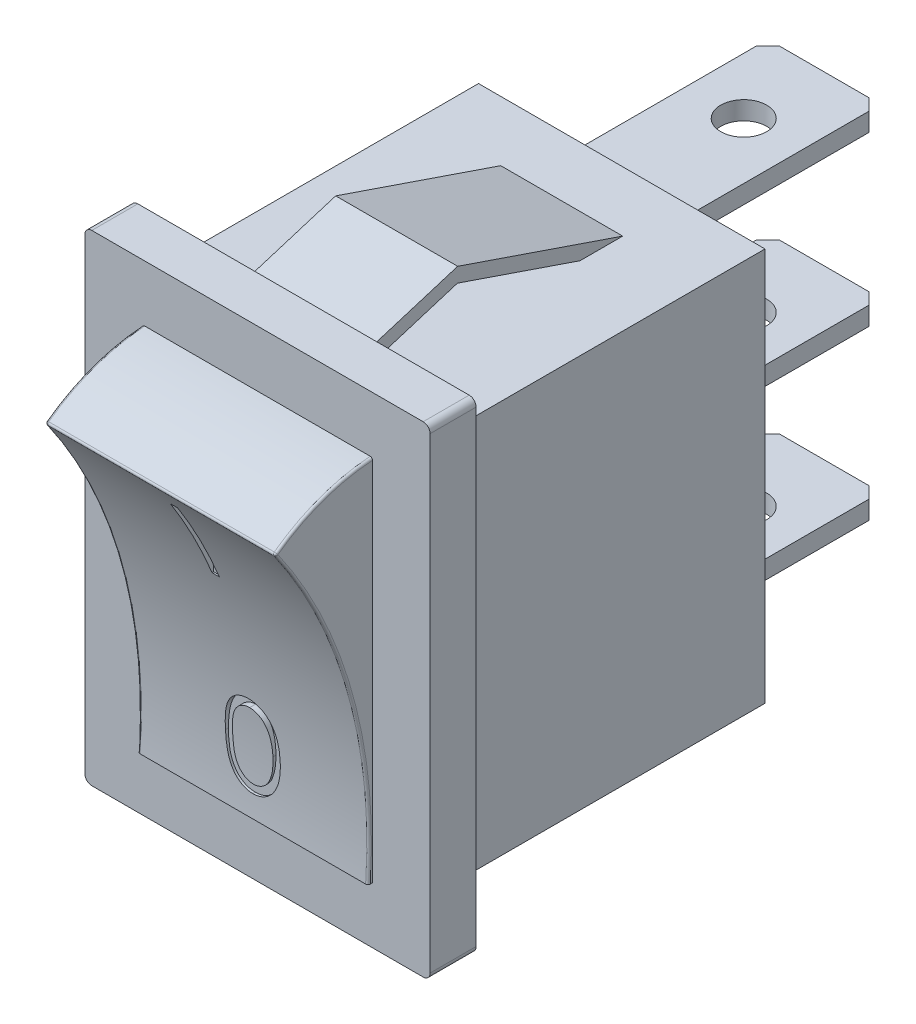
SolidWorks part; units mm, degrees
ref_plane "Front Plane" through (0, 0, 0) normal (0, 0, 1) x (1, 0, 0)
ref_plane "Top Plane" through (0, 0, 0) normal (0, 1, 0) x (1, 0, 0)
ref_plane "Right Plane" through (0, 0, 0) normal (1, 0, 0) x (0, 0, -1)
sketch "Sketch1" plane through (0, 0, 0) normal (0, 0, 1) x (1, 0, 0)
  line L1 (6.225, -8.55) -> (-6.225, -8.55)
  line L2 (6.225, -8.55) -> (6.225, 8.55)
  line L3 (6.225, 8.55) -> (-6.225, 8.55)
  line L4 (-6.225, -8.55) -> (-6.225, 8.55)
  line L5 (6.225, -8.55) -> (-6.225, 8.55) construction
  line L6 (6.225, 8.55) -> (-6.225, -8.55) construction
  point P0 (0, 0)
  dimension "D1" = 12.45
  dimension "D2" = 17.1
extrude "Boss-Extrude1" add sketch "Sketch1" against normal blind 13.83
sketch "Sketch2" plane through (0, 0, 0) normal (0, 0, 1) x (1, 0, 0)
  line L5 (-6.225, -8.55) -> (6.225, -8.55) construction
  line L6 (6.225, -8.55) -> (6.225, 8.55) construction
  line L12 (-7.5, 10.45) -> (-7.5, -10.45)
  line L13 (-7.5, -10.45) -> (7.5, -10.45)
  line L14 (7.5, -10.45) -> (7.5, 10.45)
  line L15 (7.5, 10.45) -> (-7.5, 10.45)
  dimension "D2" = 1.9
  dimension "D1" = 20.9
  dimension "D3" = 15
  dimension "D4" = 1.275
extrude "Boss-Extrude2" add sketch "Sketch2" along normal blind 2
sketch "Sketch3" plane through (0, 0, 0) normal (1, 0, 0) x (0, 0, -1)
  line L0 (0, 9.75) -> (4.0487, 11)
  line L1 (0, -10.45) -> (0, 10.45) construction
  line L2 (4.0487, 11) -> (11.2212, 8.55)
  line L3 (13.83, 8.55) -> (0, 8.55) construction
  line L4 (11.2212, 8.55) -> (9.365, 8.55)
  line L5 (9.365, 8.55) -> (4.0394, 10.3692)
  line L6 (4.0394, 10.3692) -> (0, 9.1221)
  line L7 (0, 9.1221) -> (0, 9.75)
  line L8 (0, 0) -> (9.1705, 0) construction
  line L9 (0, -9.1221) -> (0, -9.75)
  line L10 (4.0394, -10.3692) -> (0, -9.1221)
  line L11 (9.365, -8.55) -> (4.0394, -10.3692)
  line L12 (11.2212, -8.55) -> (9.365, -8.55)
  line L13 (4.0487, -11) -> (11.2212, -8.55)
  line L14 (0, -9.75) -> (4.0487, -11)
  dimension "D1" = 9.75
  dimension "D2" = 0.6
  dimension "D3" = 0.6
  dimension "D4" = 11
extrude "Boss-Extrude3" add sketch "Sketch3" along normal mid plane 5.3
sketch "Sketch4" plane through (0, 0, -13.83) normal (0, 0, -1) x (-1, 0, 0)
  line L1 (2.45, -6.9) -> (-2.45, -6.9)
  line L2 (2.45, -6.9) -> (2.45, -7.7)
  line L3 (2.45, -7.7) -> (-2.45, -7.7)
  line L4 (-2.45, -6.9) -> (-2.45, -7.7)
  line L5 (2.45, -6.9) -> (-2.45, -7.7) construction
  line L6 (2.45, -7.7) -> (-2.45, -6.9) construction
  line L7 (2.45, 0.4) -> (-2.45, 0.4)
  line L8 (2.45, 0.4) -> (2.45, -0.4)
  line L9 (2.45, -0.4) -> (-2.45, -0.4)
  line L10 (-2.45, 0.4) -> (-2.45, -0.4)
  line L11 (2.45, 0.4) -> (-2.45, -0.4) construction
  line L12 (2.45, -0.4) -> (-2.45, 0.4) construction
  line L13 (2.45, 7.7) -> (-2.45, 7.7)
  line L14 (2.45, 7.7) -> (2.45, 6.9)
  line L15 (2.45, 6.9) -> (-2.45, 6.9)
  line L16 (-2.45, 7.7) -> (-2.45, 6.9)
  line L17 (2.45, 7.7) -> (-2.45, 6.9) construction
  line L18 (2.45, 6.9) -> (-2.45, 7.7) construction
  point P0 (0, -7.3)
  point P5 (0, 0)
  point P11 (0, 7.3)
  dimension "D1" = 0
  dimension "D2" = 0
  dimension "D3" = 6.5
  dimension "D4" = 6.5
extrude "Boss-Extrude4" add sketch "Sketch4" along normal blind 8.8
chamfer "Chamfer1" distance 0.5 angle 45 6 edges at (2.45, -7.3, -22.63) (-2.45, -7.3, -22.63) (2.45, 0, -22.63) (-2.45, 0, -22.63) (2.45, 7.3, -22.63) (-2.45, 7.3, -22.63)
sketch "Sketch5" plane through (0, 7.7, 0) normal (0, 1, 0) x (1, 0, 0)
  line L0 (-1.95, 22.63) -> (1.95, 22.63) construction
  circle A0 centre (0, 19.13) radius 1
  dimension "D1" = 2
  dimension "D2" = 3.5
extrude "Cut-Extrude1" cut sketch "Sketch5" against normal through all
sketch "Sketch6" plane through (0, 0, 0) normal (1, 0, 0) x (0, 0, -1)
  line L1 (-2, -10.45) -> (-2, 10.45) construction
  line L2 (0, 0) -> (5.6681, 0) construction
  line L4 (-2, 8) -> (-2, -8)
  line L5 (-2, -8) -> (-2.2, -8)
  arc A0 (-6.25, 6.4253) -> (-2.2, -8) centre (-24.4479, -6.4651) cw
  arc A1 (-6.25, 6.4253) -> (-2, 8) centre (-1.4768, 0.0654) cw
  dimension "D1" = 8
  dimension "D2" = 4.25
  dimension "D3" = 0.2
extrude "Boss-Extrude5" add sketch "Sketch6" along normal mid plane 10
ref_plane "Plane1" through (0, 0, 5) normal (0, 0, 1) x (1, 0, 0)
fillet "Fillet2" radius 0.1 5 edges at (5, -0.437, 2.9773) (-5, -0.437, 2.9773) (-5, 7.5219, 4.2396) (0, 6.4253, 6.25) (5, 7.5219, 4.2396)
ref_plane "Plane2" through (0, 0, 6.25) normal (0, 0, 1) x (1, 0, 0)
sketch "Sketch7" plane through (0, 0, 6.25) normal (0, 0, 1) x (1, 0, 0)
  line L0 (-3.5, -7) -> (3.5, -7) construction
  text T0 "0"
  dimension "D1" = 7
  dimension "D2" = 3.5
  dimension "D3" = 7
extrude "Cut-Extrude2" cut sketch "Sketch7" against normal blind 4.2
sketch "Sketch8" plane through (0, 0, 6.25) normal (0, 0, 1) x (1, 0, 0)
  line L0 (-3.5, 2) -> (3.5, 2) construction
  text T0 "I"
  dimension "D1" = 7
  dimension "D2" = 3.5
  dimension "D3" = 2
extrude "Cut-Extrude3" cut sketch "Sketch8" against normal blind 2.5
fillet "Fillet3" radius 0.3 4 edges at (-7.5, -10.45, 1) (7.5, -10.45, 1) (-7.5, 10.45, 1) (7.5, 10.45, 1)
